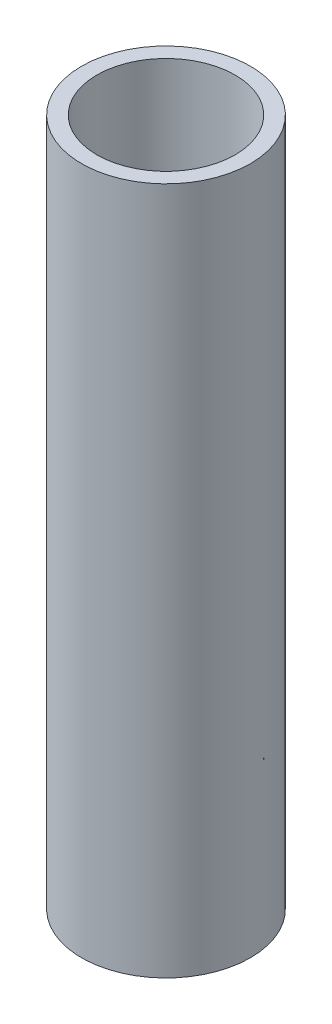
SolidWorks part; units mm, degrees
material "AISI 316 Stainless Steel Sheet (SS)"
ref_plane "Front Plane" through (0, 0, 0) normal (0, 0, 1) x (1, 0, 0)
ref_plane "Top Plane" through (0, 0, 0) normal (0, 1, 0) x (1, 0, 0)
ref_plane "Right Plane" through (0, 0, 0) normal (1, 0, 0) x (0, 0, -1)
sketch "Sketch1" plane through (0, 37.4527, 0) normal (0, -1, 0) x (1, 0, 0)
  circle A0 centre (0.7, -1.6) radius 0.7366
  circle A1 centre (0.7, -1.6) radius 0.6033
  dimension "D1" = 1.4732
  dimension "D2" = 1.2065
extrude "Boss-Extrude1" add sketch "Sketch1" along normal up to surface (6 mm away)
